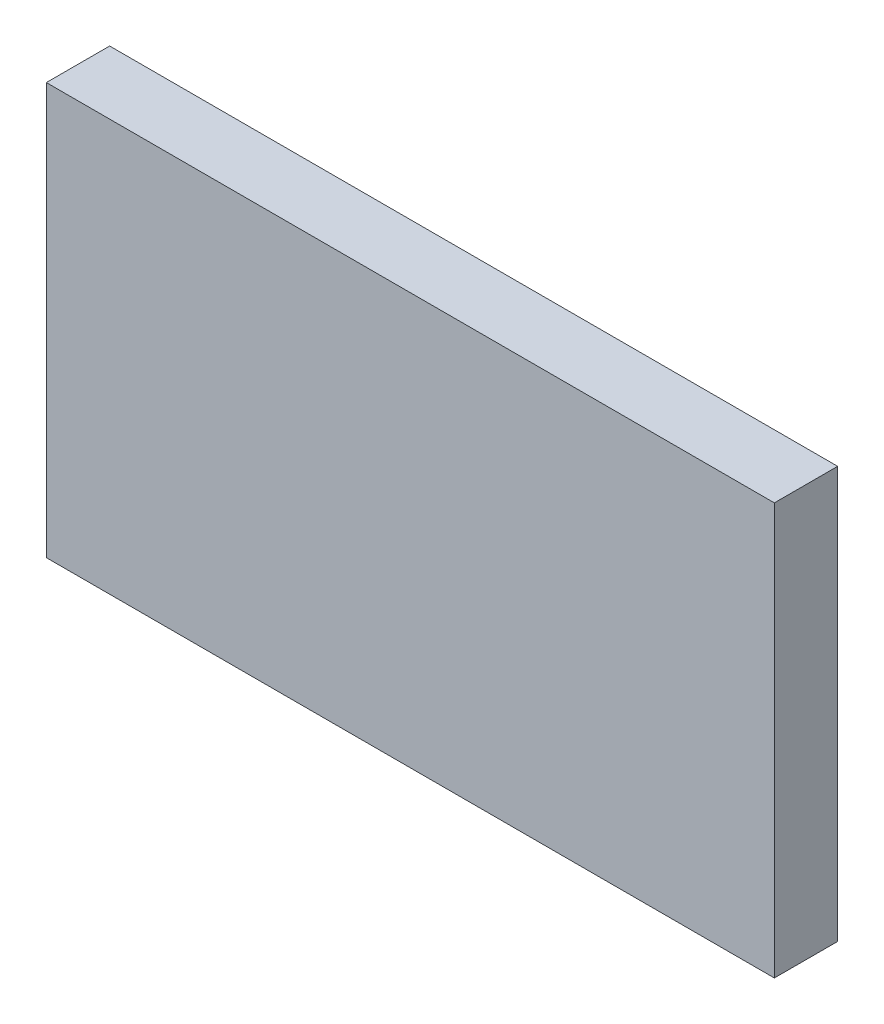
SolidWorks part; units mm, degrees
ref_plane "Plano frontal" through (0, 0, 0) normal (0, 0, 1) x (1, 0, 0)
ref_plane "Plano superior" through (0, 0, 0) normal (0, 1, 0) x (1, 0, 0)
ref_plane "Plano direito" through (0, 0, 0) normal (1, 0, 0) x (0, 0, -1)
sketch "Esboço1" plane through (0, 0, 0) normal (0, 0, 1) x (1, 0, 0)
  line L1 (-11.5, -6.5) -> (11.5, -6.5)
  line L2 (-11.5, -6.5) -> (-11.5, 6.5)
  line L3 (-11.5, 6.5) -> (11.5, 6.5)
  line L4 (11.5, -6.5) -> (11.5, 6.5)
  line L5 (-11.5, -6.5) -> (11.5, 6.5) construction
  line L6 (-11.5, 6.5) -> (11.5, -6.5) construction
  point P0 (0, 0)
  dimension "D1" = 13
  dimension "D2" = 23
extrude "Ressalto-extrusão1" add sketch "Esboço1" along normal blind 2
